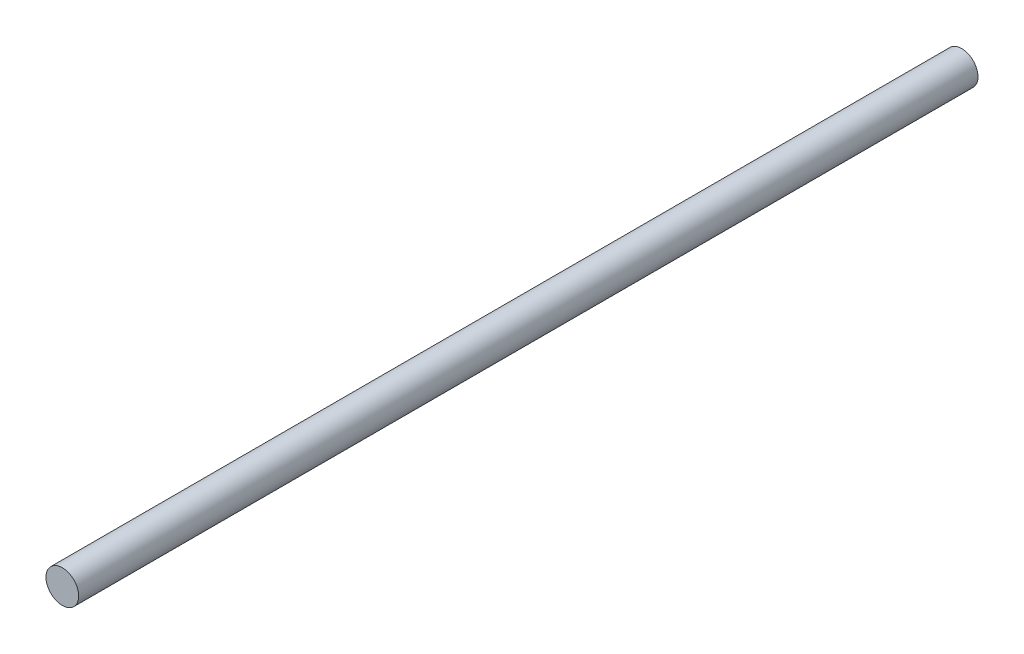
SolidWorks part; units mm, degrees
ref_plane "前视基准面" through (0, 0, 0) normal (0, 0, 1) x (1, 0, 0)
ref_plane "上视基准面" through (0, 0, 0) normal (0, 1, 0) x (1, 0, 0)
ref_plane "右视基准面" through (0, 0, 0) normal (1, 0, 0) x (0, 0, -1)
sketch "草图1" plane through (0, 0, 0) normal (0, 0, 1) x (1, 0, 0)
  circle A0 centre (0, 0) radius 1
  dimension "D1" = 2
extrude "凸台-拉伸1" add sketch "草图1" along normal blind 55
